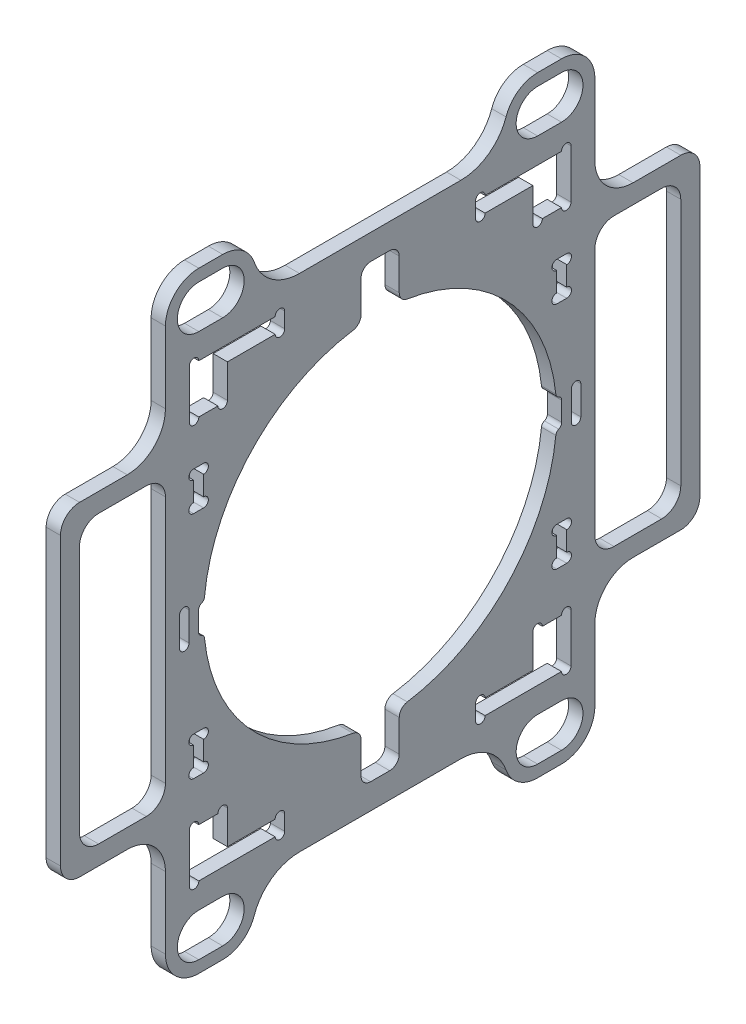
SolidWorks part; units mm, degrees
material "Thornel Mat VMA"
ref_plane "前视基准面" through (0, 0, 0) normal (0, 0, 1) x (1, 0, 0)
ref_plane "上视基准面" through (0, 0, 0) normal (0, 1, 0) x (1, 0, 0)
ref_plane "右视基准面" through (0, 0, 0) normal (1, 0, 0) x (0, 0, -1)
sketch "草图1" plane through (0, 0, 0) normal (1, 0, 0) x (0, 0, -1)
  line L5 (45, -52.5) -> (-45, -52.5)
  line L6 (45, -52.5) -> (45, 52.5)
  line L7 (45, 52.5) -> (-45, 52.5)
  line L8 (-45, -52.5) -> (-45, 52.5)
  line L9 (45, -52.5) -> (-45, 52.5) construction
  line L10 (45, 52.5) -> (-45, -52.5) construction
  circle A0 centre (0, 0) radius 37
  point P3 (0, 0)
  dimension "D1" = 74
  dimension "D2" = 105
  dimension "D3" = 90
extrude "凸台-拉伸1" add sketch "草图1" along normal blind 3
fillet "圆角1" radius 3 4 edges at (1.5, 52.5, -45) (1.5, 52.5, 45) (1.5, -52.5, 45) (1.5, -52.5, -45)
sketch "草图4" plane through (0, 0, 0) normal (-1, 0, 0) x (0, 0, 1)
  line L9 (-32, -44) -> (-20, -44)
  line L10 (-40, -44) -> (-40, -47.2)
  line L11 (-40, -47.2) -> (-20, -47.2)
  line L12 (-20, -44) -> (-20, -47.2)
  line L14 (-40, -44) -> (-40, -37)
  line L15 (-40, -37) -> (-32, -37)
  line L16 (-32, -44) -> (-32, -37)
  circle A1 centre (0, 0) radius 37 construction
  dimension "D1" = 37
  dimension "D6" = 40
  dimension "D2" = 7
  dimension "D3" = 3.2
  dimension "D4" = 20
  dimension "D5" = 8
  dimension "D7" = 10.2
extrude "切除-拉伸2" cut sketch "草图4" against normal blind 10
mirror "镜向1" about plane through (0, 0, 0) normal (0, 0, 1) of "切除-拉伸2"
mirror "镜向2" about plane through (0, 0, 0) normal (0, 1, 0) of "镜向1", "切除-拉伸2"
sketch "草图5" plane through (0, 0, 0) normal (-1, 0, 0) x (0, 0, 1)
  line L0 (-40, 47.2) -> (-20, 47.2) construction
  line L1 (4, 32.898) -> (-4, 32.898)
  line L2 (4, 32.898) -> (4, 47.2)
  line L3 (4, 47.2) -> (-4, 47.2)
  line L4 (-4, 32.898) -> (-4, 47.2)
  line L5 (4, 32.898) -> (-4, 47.2) construction
  line L6 (4, 47.2) -> (-4, 32.898) construction
  line L7 (0, 0) -> (0, 40.049) construction
  point P0 (0, 40.049)
  dimension "D1" = 8
extrude "切除-拉伸3" cut sketch "草图5" against normal blind 10
mirror "镜向3" about plane through (0, 0, 0) normal (0, 1, 0) of "切除-拉伸3"
sketch "草图6" plane through (0, 0, 0) normal (-1, 0, 0) x (0, 0, 1)
  line L0 (39.1, -24.05) -> (40.1, -24.05) construction
  line L1 (37, -28.1) -> (39.1, -28.1)
  line L2 (37, -28.1) -> (37, -20)
  line L3 (37, -20) -> (39.1, -20)
  line L4 (39.1, -28.1) -> (39.1, -20)
  line L5 (41.1, -26.05) -> (39.1, -26.05)
  line L6 (41.1, -26.05) -> (41.1, -22.05)
  line L7 (41.1, -22.05) -> (39.1, -22.05)
  line L8 (39.1, -26.05) -> (39.1, -22.05)
  line L9 (41.1, -26.05) -> (39.1, -22.05) construction
  line L10 (41.1, -22.05) -> (39.1, -26.05) construction
  point P4 (38.05, -20)
  point P6 (40.1, -24.05)
  dimension "D1" = 37
  dimension "D2" = 20
  dimension "D3" = 8.1
  dimension "D4" = 2.1
  dimension "D5" = 2
  dimension "D6" = 4
extrude "切除-拉伸4" cut sketch "草图6" against normal blind 10 contours L1 L4 L3 L2
mirror "镜向4" about plane through (0, 0, 0) normal (0, 1, 0) of "切除-拉伸4"
mirror "镜向5" about plane through (0, 0, 0) normal (0, 0, 1) of "镜向4", "切除-拉伸4"
sketch "草图7" plane through (0, 0, 0) normal (-1, 0, 0) x (0, 0, 1)
  line L0 (38.05, -20) -> (38.05, 20) construction
  line L1 (42.05, -3) -> (40.05, -3)
  line L2 (42.05, -3) -> (42.05, 3)
  line L3 (42.05, 3) -> (40.05, 3)
  line L4 (40.05, -3) -> (40.05, 3)
  line L5 (42.05, -3) -> (40.05, 3) construction
  line L6 (42.05, 3) -> (40.05, -3) construction
  line L7 (39.1, -20) -> (37, -20) construction
  line L8 (39.1, 20) -> (37, 20) construction
  line L9 (38.05, 0) -> (41.05, 0) construction
  line L10 (32.6898, 0) -> (38.05, 0) construction
  line L11 (27.3296, -3) -> (37.05, -3)
  line L12 (27.3296, -3) -> (27.3296, 3)
  line L13 (27.3296, 3) -> (37.05, 3)
  line L14 (38.05, -2) -> (38.05, 2)
  line L15 (27.3296, -3) -> (38.05, 3) construction
  line L16 (27.3296, 3) -> (38.05, -3) construction
  circle A0 centre (41.05, 3) radius 1
  circle A1 centre (41.05, -3) radius 1
  arc A2 (37.05, 3) -> (38.05, 2) centre (37.05, 2) cw
  arc A3 (37.05, -3) -> (38.05, -2) centre (37.05, -2) ccw
  point P0 (41.05, 0)
  point P13 (32.6898, 0)
  dimension "D5" = 2
  dimension "D6" = 1
  dimension "D1" = 3
  dimension "D2" = 2
  dimension "D3" = 6
  dimension "D4" = 6
extrude "切除-拉伸5" cut sketch "草图7" against normal blind 10 contours L11 L14 L13 L12 | L3 A0 | L1 A1
mirror "镜向6" about plane through (0, 0, 0) normal (0, 0, 1) of "切除-拉伸5"
sketch "草图8" plane through (0, 0, 0) normal (-1, 0, 0) x (0, 0, 1)
  line L0 (45, 49.5) -> (45, -49.5) construction
  line L1 (63, -30) -> (45, -30)
  line L2 (63, -30) -> (63, 30)
  line L3 (63, 30) -> (45, 30)
  line L4 (45, -30) -> (45, 30)
  line L5 (63, -30) -> (45, 30) construction
  line L6 (63, 30) -> (45, -30) construction
  line L7 (0, 0) -> (70.7854, 0) construction
  line L9 (67, -34) -> (45, -34)
  line L10 (67, -34) -> (67, 34)
  line L11 (67, 34) -> (45, 34)
  line L12 (45, -34) -> (45, 34)
  line L13 (67, -34) -> (45, 34) construction
  line L14 (67, 34) -> (45, -34) construction
  point P0 (54, 0)
  point P10 (56, 0)
  dimension "D1" = 60
  dimension "D2" = 18
  dimension "D3" = 4
  dimension "D4" = 4
extrude "凸台-拉伸2" add sketch "草图8" against normal blind 3 contours L12 L9 L10 L11 L3 L2 L1
mirror "镜向7" about plane through (0, 0, 0) normal (0, 0, 1) of "凸台-拉伸2"
fillet "圆角2" radius 4 12 edges at (1.5, -34, -67) (1.5, -30, -63) (1.5, -30, -45) (1.5, 30, -45) (1.5, 30, -63) (1.5, 34, -67) (1.5, -34, 67) (1.5, 34, 67) (1.5, 30, 63) (1.5, 30, 45) (1.5, -30, 63) (1.5, -30, 45)
fillet "圆角3" radius 8 4 edges at (1.5, -34, 45) (1.5, 34, 45) (1.5, 34, -45) (1.5, -34, -45)
sketch "草图9" plane through (0, 0, 0) normal (-1, 0, 0) x (0, 0, 1)
  line L0 (33, 57) -> (38, 57) construction
  line L1 (33, 64) -> (38, 64)
  line L2 (33, 57) -> (38, 57) construction
  line L3 (33, 61.5) -> (38, 61.5)
  line L4 (33, 52.5) -> (38, 52.5)
  line L5 (0, 0) -> (35, 0) construction
  line L6 (33, 50) -> (38, 50)
  line L7 (-42, 52.5) -> (42, 52.5) construction
  line L8 (45, 49.5) -> (45, 42) construction
  line L9 (45, 57) -> (45, 47.2477)
  line L10 (45, 47.2477) -> (26, 47.2477)
  line L11 (26, 47.2477) -> (26, 57)
  line L12 (33, -57) -> (38, -57) construction
  line L13 (33, -64) -> (38, -64)
  line L14 (33, -50) -> (38, -50)
  line L15 (33, -57) -> (38, -57) construction
  line L16 (33, -61.5) -> (38, -61.5)
  line L17 (33, -52.5) -> (38, -52.5)
  line L18 (26, -47.2477) -> (26, -57)
  line L19 (45, -47.2477) -> (26, -47.2477)
  line L20 (45, -57) -> (45, -47.2477)
  arc A4 (33, 61.5) -> (33, 52.5) centre (33, 57) ccw
  arc A5 (38, 52.5) -> (38, 61.5) centre (38, 57) ccw
  arc A6 (33, 64) -> (33, 50) centre (33, 57) ccw
  arc A7 (38, 50) -> (38, 64) centre (38, 57) ccw
  arc A8 (33, -64) -> (33, -50) centre (33, -57) cw
  arc A9 (38, -50) -> (38, -64) centre (38, -57) cw
  arc A10 (33, -61.5) -> (33, -52.5) centre (33, -57) cw
  arc A11 (38, -52.5) -> (38, -61.5) centre (38, -57) cw
  point P2 (35.5, 57)
  point P8 (35.5, 57)
  point P28 (35.5, -57)
  point P35 (35.5, -57)
  dimension "D1" = 4.5
  dimension "D2" = 4.5
  dimension "D3" = 7
  dimension "D4" = 5
extrude "凸台-拉伸3" add sketch "草图9" against normal blind 3 contours A9 L14 A8 L13 L17 A11 L16 A10 | L14 A9 L20 L19 L18 A8 | A7 L1 A6 L6 A5 L4 A4 L3 | A7 L6 A6 L11 L10 L9
fillet "圆角4" radius 10 2 edges at (1.5, 52.5, 26) (1.5, -52.5, 26)
mirror "镜向8" about plane through (0, 0, 0) normal (0, 0, 1) of "圆角4", "凸台-拉伸3"
fillet "圆角5" radius 1 4 edges at (1.5, 3, -36.8782) (1.5, -3, -36.8782) (1.5, 3, 36.8782) (1.5, -3, 36.8782)
sketch "草图10" plane through (0, 0, 0) normal (-1, 0, 0) x (0, 0, 1)
  line L0 (20, -44) -> (32, -44) construction
  line L1 (40, -47.2) -> (20, -47.2) construction
  line L2 (32, -37) -> (40, -37) construction
  line L3 (20, -47.2) -> (20, -44) construction
  line L4 (40, -37) -> (40, -47.2) construction
  line L5 (37, -28.1) -> (37, -20) construction
  line L6 (37, -20) -> (39.1, -20) construction
  line L7 (37, -28.1) -> (39.1, -28.1) construction
  line L8 (38.05, -28.1) -> (38.05, -20) construction
  circle A0 centre (21, -44) radius 1
  circle A1 centre (21, -47.2) radius 1
  circle A2 centre (39, -47.2) radius 1
  circle A3 centre (39, -37) radius 1
  circle A4 centre (33, -37) radius 1
  circle A5 centre (37, -21) radius 1
  circle A6 centre (37, -27.1) radius 1
  circle A7 centre (39.1, -27.1) radius 1
  circle A8 centre (39.1, -21) radius 1
  dimension "D1" = 2
  dimension "D2" = 2
  dimension "D3" = 2
  dimension "D4" = 2
  dimension "D5" = 2
  dimension "D6" = 2
  dimension "D7" = 2
extrude "切除-拉伸6" cut sketch "草图10" against normal blind 10 contours A6 | A7 | A8 | A5 | A3 | A4 | A2 | A1 | A0
mirror "镜向9" about plane through (0, 0, 0) normal (0, 1, 0) of "切除-拉伸6"
mirror "镜向10" about plane through (0, 0, 0) normal (0, 0, 1) of "镜向9", "切除-拉伸6"
fillet "圆角6" radius 2 8 edges at (1.5, 47.2, 4) (1.5, 47.2, -4) (1.5, 36.7831, -4) (1.5, 36.7831, 4) (1.5, -36.7831, 4) (1.5, -47.2, 4) (1.5, -47.2, -4) (1.5, -36.7831, -4)
